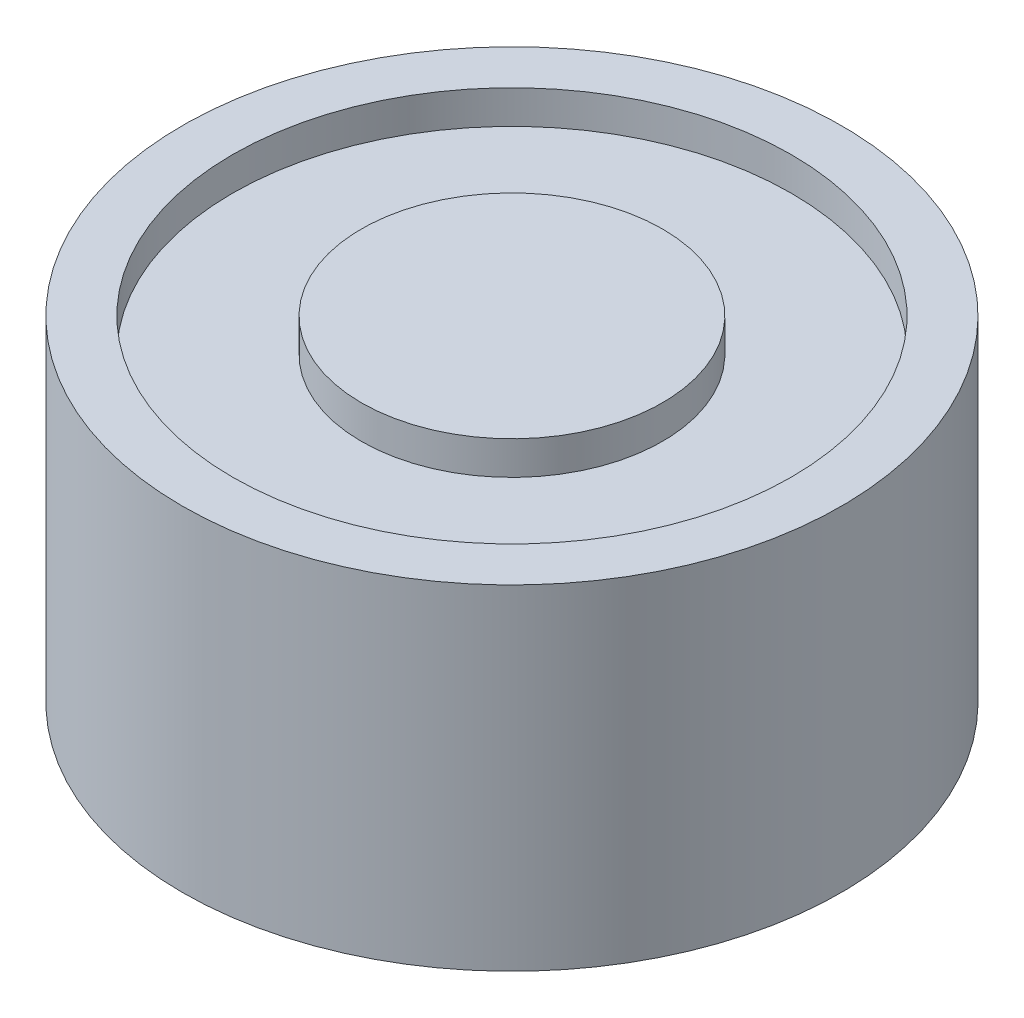
SolidWorks part; units mm, degrees
ref_plane "Front" through (0, 0, 0) normal (0, 0, 1) x (1, 0, 0)
ref_plane "Top" through (0, 0, 0) normal (0, 1, 0) x (1, 0, 0)
ref_plane "Right" through (0, 0, 0) normal (1, 0, 0) x (0, 0, -1)
sketch "Sketch1" plane through (0, 0, 0) normal (0, 1, 0) x (1, 0, 0)
  circle A0 centre (0, 0) radius 19.7
  dimension "D1" = 39.4
extrude "Boss-Extrude1" add sketch "Sketch1" along normal blind 20 contours A0
sketch "Sketch2" plane through (0, 20, 0) normal (0, 1, 0) x (1, 0, 0)
  circle A0 centre (0, 0) radius 16.7
  circle A1 centre (0, 0) radius 9
  circle A2 centre (0, 0) radius 19.7 construction
  dimension "D1" = 3
  dimension "D2" = 18
extrude "Cut-Extrude1" cut sketch "Sketch2" against normal blind 2
